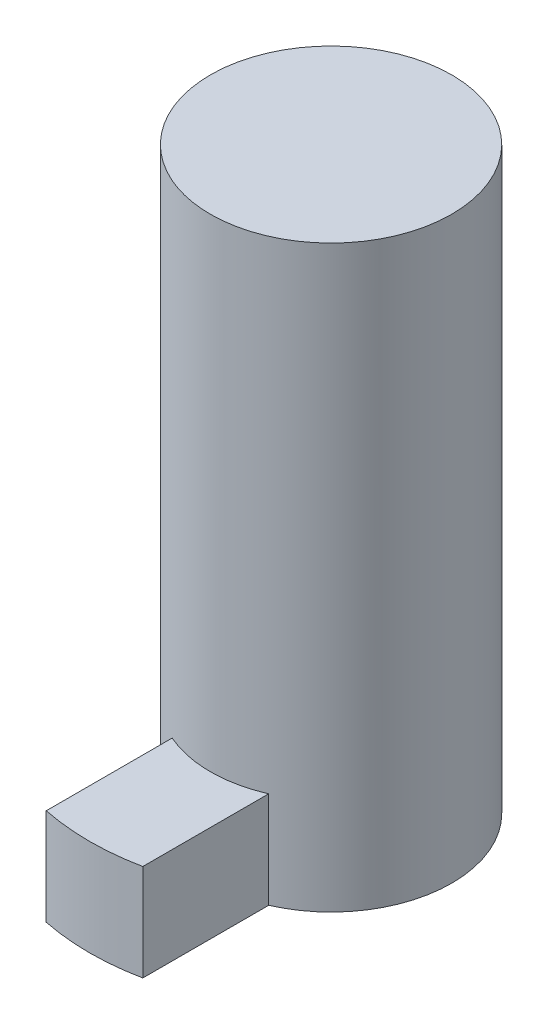
SolidWorks part; units mm, degrees
ref_plane "Front Plane" through (0, 0, 0) normal (0, 0, 1) x (1, 0, 0)
ref_plane "Top Plane" through (0, 0, 0) normal (0, 1, 0) x (1, 0, 0)
ref_plane "Right Plane" through (0, 0, 0) normal (1, 0, 0) x (0, 0, -1)
sketch "Sketch1" plane through (0, 0, 0) normal (0, 1, 0) x (1, 0, 0)
  circle A0 centre (0, 0) radius 1.25
  dimension "D1" = 2.5
extrude "Boss-Extrude1" add sketch "Sketch1" along normal blind 6
sketch "Sketch3" plane through (0, 0, 0) normal (0, -1, 0) x (1, 0, 0)
  line L0 (0, 0) -> (0, 1.25) construction
  line L3 (-0.5, 2.4495) -> (-0.5, 1.1456)
  line L5 (0.5, 2.4495) -> (0.5, 1.1456)
  circle A0 centre (0, 0) radius 1.25 construction
  arc A1 (0.5, 1.1456) -> (-0.5, 1.1456) centre (0, 0) ccw
  arc A2 (0.5, 2.4495) -> (-0.5, 2.4495) centre (0, 0) ccw
  dimension "D2" = 5
extrude "Boss-Extrude3" add sketch "Sketch3" against normal blind 1
